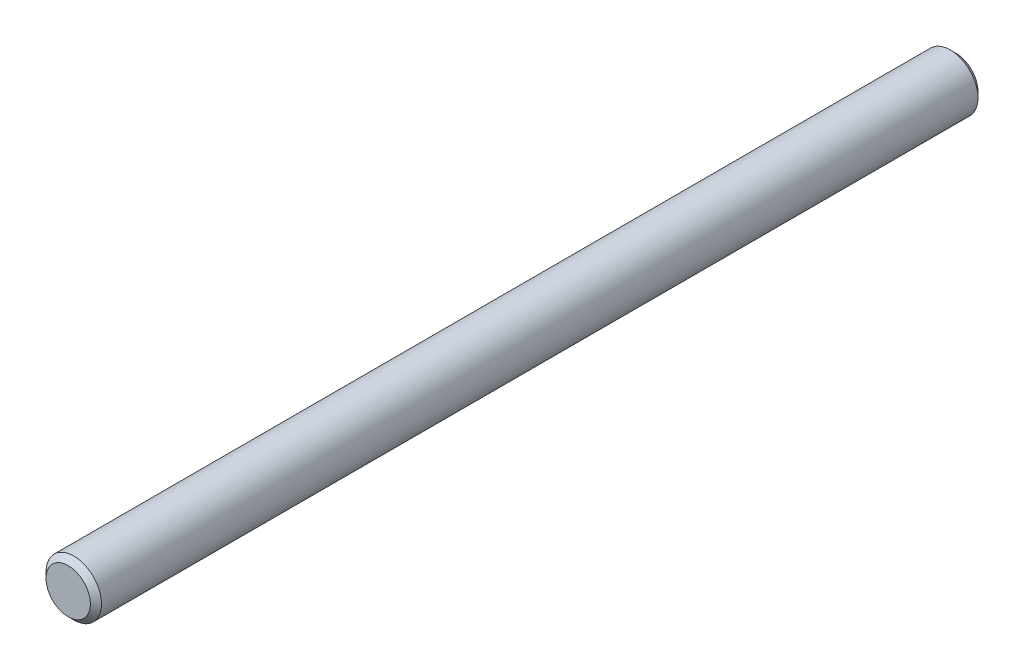
SolidWorks part; units mm, degrees
ref_plane "前视基准面" through (0, 0, 0) normal (0, 0, 1) x (1, 0, 0)
ref_plane "上视基准面" through (0, 0, 0) normal (0, 1, 0) x (1, 0, 0)
ref_plane "右视基准面" through (0, 0, 0) normal (1, 0, 0) x (0, 0, -1)
other "Configuration Table"
sketch "草图1" plane through (0, 0, 0) normal (0, 0, 1) x (1, 0, 0)
  circle A0 centre (0, 0) radius 2.5
  dimension "D1" = 5
extrude "凸台-拉伸1" add sketch "草图1" along normal blind 80
chamfer "倒角1" distance 0.5 angle 45 2 edges at (2.5, 0, 80) (2.5, 0, 0)
